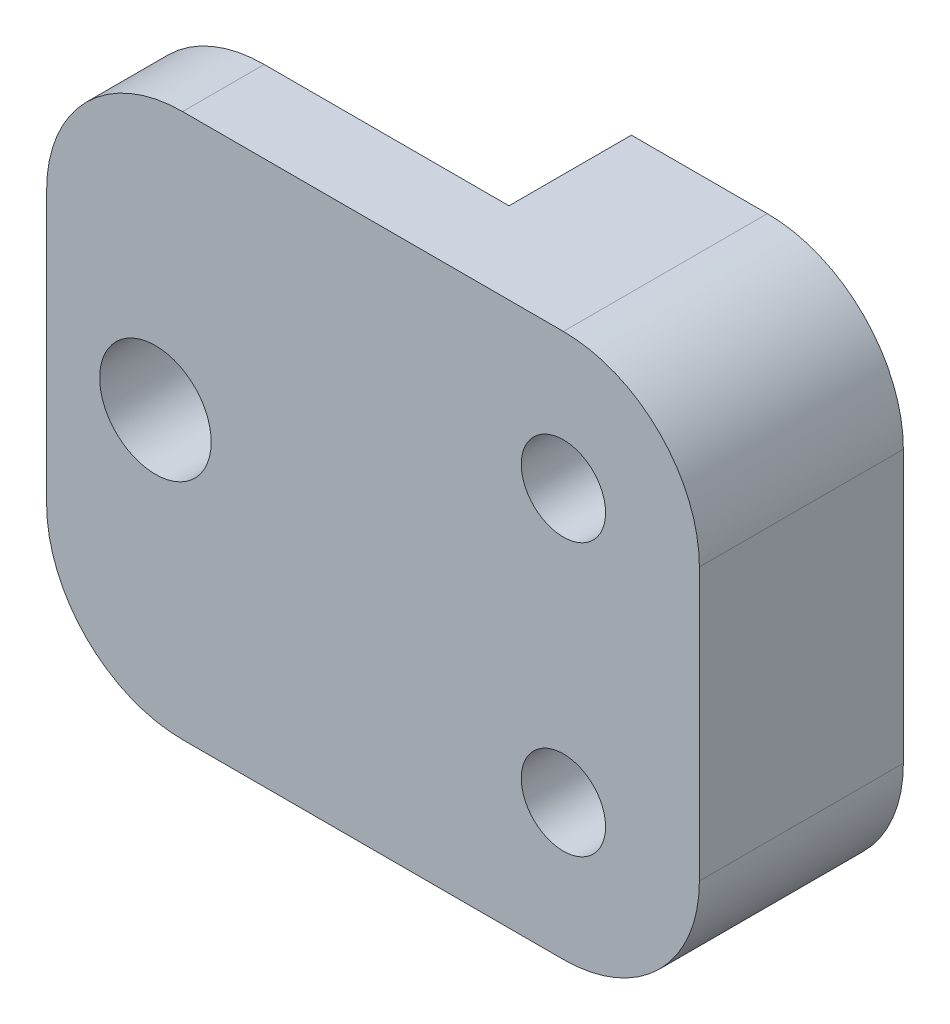
SolidWorks part; units mm, degrees
ref_plane "Ebene vorne" through (0, 0, 0) normal (0, 0, 1) x (1, 0, 0)
ref_plane "Ebene oben" through (0, 0, 0) normal (0, 1, 0) x (1, 0, 0)
ref_plane "Ebene rechts" through (0, 0, 0) normal (1, 0, 0) x (0, 0, -1)
sketch "Skizze1" plane through (0, 0, 0) normal (0, 1, 0) x (1, 0, 0)
  line L3 (2, -4.5) -> (-12, -4.5)
  line L4 (-12, -4.5) -> (-12, -7.5)
  line L5 (-12, -7.5) -> (12, -7.5)
  line L8 (2, 0) -> (12, 0)
  line L9 (2, 0) -> (2, -4.5)
  line L10 (12, 0) -> (12, -7.5)
  point P1 (0, -7.5)
  dimension "D4" = 14
  dimension "D1" = 3
  dimension "D2" = 4.5
  dimension "D3" = 10
extrude "Aufsatz-Linear austragen1" add sketch "Skizze1" along normal blind 20
sketch "Skizze2" plane through (0, 0, 7.5) normal (0, 0, 1) x (1, 0, 0)
  line L0 (7, 15) -> (7, 5)
  line L1 (-12, 20) -> (-12, 0) construction
  line L3 (-12, 10) -> (12, 10) construction
  line L5 (12, 20) -> (12, 0) construction
  circle A0 centre (-8, 10) radius 2.05
  circle A1 centre (7, 15) radius 1.55
  circle A2 centre (7, 5) radius 1.55
  point P9 (7, 10)
  dimension "D3" = 4.1
  dimension "D2" = 3.1
  dimension "D4" = 3.1
  dimension "D1" = 4
  dimension "D5" = 5
  dimension "D6" = 10
extrude "Schnitt-Linear austragen1" cut sketch "Skizze2" against normal through all
fillet "Verrundung1" radius 5 4 edges at (-12, 0, 6) (-12, 20, 6) (12, 0, 3.75) (12, 20, 3.75)
